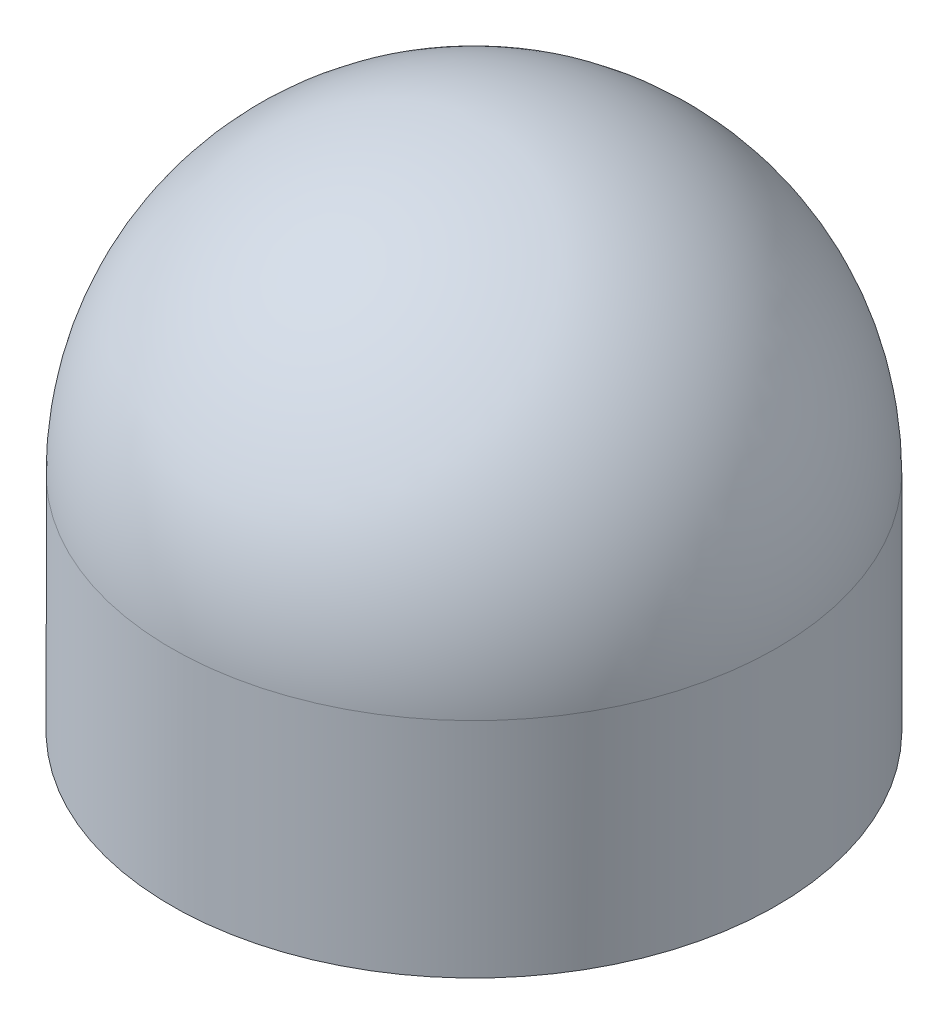
SolidWorks part; units mm, degrees
ref_plane "Front Plane" through (0, 0, 0) normal (0, 0, 1) x (1, 0, 0)
ref_plane "Top Plane" through (0, 0, 0) normal (0, 1, 0) x (1, 0, 0)
ref_plane "Right Plane" through (0, 0, 0) normal (1, 0, 0) x (0, 0, -1)
sketch "Sketch2" plane through (0, 0, 0) normal (0, 0, 1) x (1, 0, 0)
  line L0 (0, 0) -> (0, 8.25) construction
  line L1 (0, 0) -> (4.75, 0)
  line L2 (4.75, 0) -> (4.75, 3.5)
  line L3 (0, 8.25) -> (3.7937, 8.25) construction
  line L4 (0, 0) -> (0, 8.25)
  arc A0 (4.75, 3.5) -> (0, 8.25) centre (0, 3.5) ccw
  dimension "D1" = 3.5
  dimension "D2" = 9.5
revolve "Revolve1" add sketch "Sketch2" angle 360 about L4
